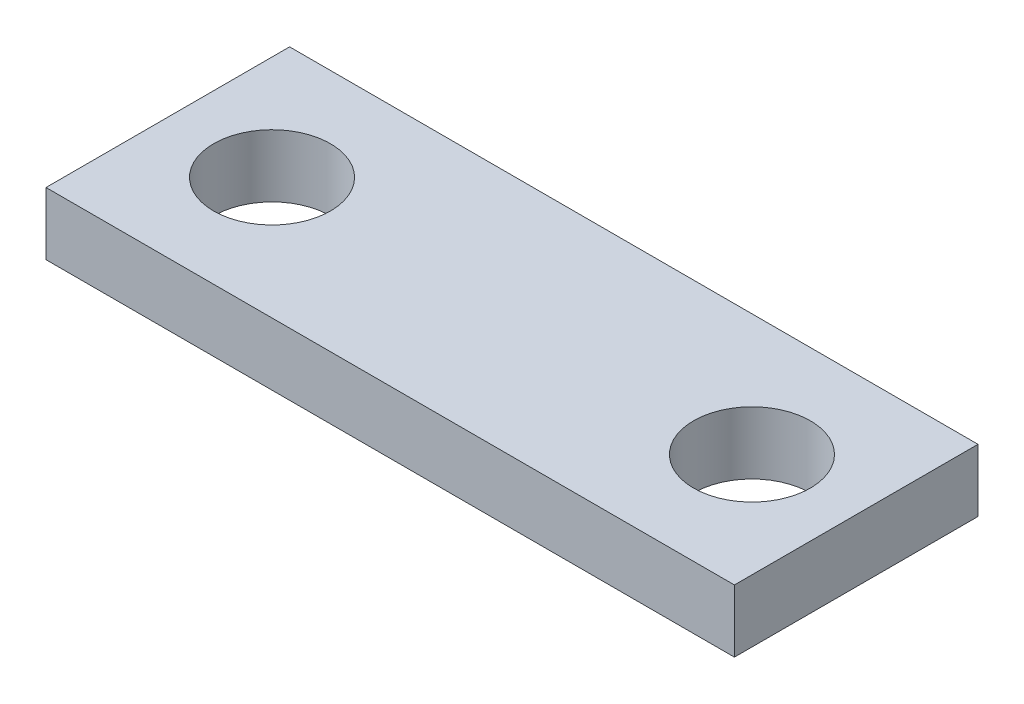
SolidWorks part; units mm, degrees
ref_plane "前基準面" through (0, 0, 0) normal (0, 0, 1) x (1, 0, 0)
ref_plane "上基準面" through (0, 0, 0) normal (0, 1, 0) x (1, 0, 0)
ref_plane "右基準面" through (0, 0, 0) normal (1, 0, 0) x (0, 0, -1)
sketch "Sketch1" plane through (0, 0, 0) normal (0, 1, 0) x (1, 0, 0)
  line L1 (-8.255, -2.921) -> (8.255, -2.921)
  line L2 (-8.255, -2.921) -> (-8.255, 2.921)
  line L3 (-8.255, 2.921) -> (8.255, 2.921)
  line L4 (8.255, -2.921) -> (8.255, 2.921)
  line L5 (-8.255, -2.921) -> (8.255, 2.921) construction
  line L6 (-8.255, 2.921) -> (8.255, -2.921) construction
  point P0 (0, 0)
  dimension "D1" = 16.51
  dimension "D2" = 5.842
extrude "Boss-Extrude1" add sketch "Sketch1" along normal blind 1.5
sketch "Sketch2" plane through (0, 1.5, 0) normal (0, 1, 0) x (1, 0, 0)
  line L0 (8.255, -2.921) -> (8.255, 2.921) construction
  line L1 (-8.255, 2.921) -> (-8.255, -2.921) construction
  circle A0 centre (-5.755, 0) radius 1.4
  circle A1 centre (5.755, 0) radius 1.4
  dimension "D3" = 2.8
  dimension "D4" = 2.8
  dimension "D1" = 2.5
  dimension "D2" = 2.5
extrude "Cut-Extrude1" cut sketch "Sketch2" against normal blind 1.5
